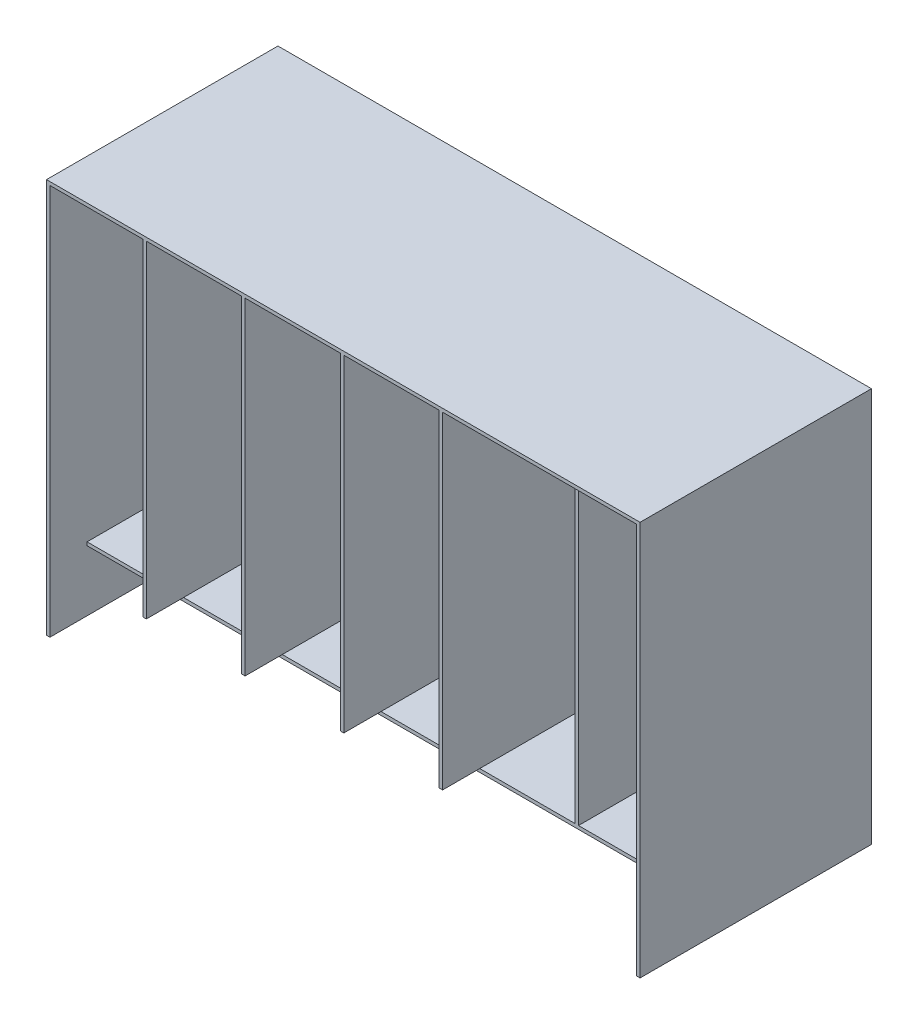
SolidWorks part; units mm, degrees
material "6061-T6 (SS)"
ref_plane "X-Y Datum" through (0, 0, 0) normal (0, 0, 1) x (1, 0, 0)
ref_plane "X-Z Datum" through (0, 0, 0) normal (0, 1, 0) x (1, 0, 0)
ref_plane "Y-Z Datum" through (0, 0, 0) normal (1, 0, 0) x (0, 0, -1)
sketch "Sketch1" plane through (0, 0, 0) normal (0, 0, 1) x (1, 0, 0)
  line L0 (-276.2265, 0) -> (276.2265, 0) construction
  line L1 (-276.2265, 154.041) -> (276.2265, 154.041)
  line L2 (-276.2265, 154.041) -> (-276.2265, -154.041)
  line L3 (-276.2265, -154.041) -> (276.2265, -154.041)
  line L4 (276.2265, 154.041) -> (276.2265, -154.041)
  line L5 (-276.2265, 154.041) -> (276.2265, -154.041) construction
  line L6 (-276.2265, -154.041) -> (276.2265, 154.041) construction
  line L7 (-275.2105, 153.025) -> (-189.6105, 153.025) construction
  line L8 (-275.2105, 153.025) -> (-275.2105, -153.025) construction
  line L9 (-275.2105, -153.025) -> (-189.6105, -153.025) construction
  line L10 (-189.6105, 153.025) -> (-189.6105, -153.025) construction
  line L11 (-275.2105, 153.025) -> (-189.6105, -153.025) construction
  line L12 (-275.2105, -153.025) -> (-189.6105, 153.025) construction
  line L13 (-188.5945, -154.041) -> (-188.5945, 154.041)
  line L14 (-279.4015, 157.216) -> (279.4015, 157.216)
  line L15 (279.4015, 157.216) -> (279.4015, -157.216)
  line L16 (-279.4015, -157.216) -> (279.4015, -157.216)
  line L17 (-279.4015, 157.216) -> (-279.4015, -157.216)
  line L18 (-185.4195, -154.041) -> (-185.4195, 154.041)
  line L19 (-188.5945, 0) -> (-185.4195, 0) construction
  line L20 (-182.2465, 153.025) -> (-182.2465, -153.025) construction
  line L21 (-182.2465, 153.025) -> (-96.6465, 153.025) construction
  line L22 (-96.6465, 153.025) -> (-96.6465, -153.025) construction
  line L23 (-182.2465, -153.025) -> (-96.6465, -153.025) construction
  line L24 (-95.6305, -154.041) -> (-95.6305, 154.041)
  line L25 (-92.4555, -154.041) -> (-92.4555, 154.041)
  line L26 (-89.2825, 153.025) -> (-89.2825, -153.025) construction
  line L27 (-89.2825, 153.025) -> (-3.6825, 153.025) construction
  line L28 (-3.6825, 153.025) -> (-3.6825, -153.025) construction
  line L29 (-89.2825, -153.025) -> (-3.6825, -153.025) construction
  line L30 (-2.6665, -154.041) -> (-2.6665, 154.041)
  line L31 (0.5085, -154.041) -> (0.5085, 154.041)
  line L32 (3.6815, 153.025) -> (3.6815, -153.025) construction
  line L33 (3.6815, 153.025) -> (89.2815, 153.025) construction
  line L34 (89.2815, 153.025) -> (89.2815, -153.025) construction
  line L35 (3.6815, -153.025) -> (89.2815, -153.025) construction
  line L36 (90.2975, -154.041) -> (90.2975, 154.041)
  line L37 (93.4725, -154.041) -> (93.4725, 154.041)
  line L38 (96.6455, 153.025) -> (96.6455, -153.025) construction
  line L39 (96.6455, 153.025) -> (182.2455, 153.025) construction
  line L40 (182.2455, 153.025) -> (182.2455, -153.025) construction
  line L41 (96.6455, -153.025) -> (182.2455, -153.025) construction
  line L42 (183.2615, -154.041) -> (183.2615, 154.041)
  line L43 (186.4365, -154.041) -> (186.4365, 154.041)
  line L44 (-182.2465, -153.025) -> (-96.6465, 153.025) construction
  line L45 (-182.2465, 153.025) -> (-96.6465, -153.025) construction
  line L46 (-89.2825, -153.025) -> (-3.6825, 153.025) construction
  line L47 (-89.2825, 153.025) -> (-3.6825, -153.025) construction
  line L48 (3.6815, -153.025) -> (89.2815, 153.025) construction
  line L49 (3.6815, 153.025) -> (89.2815, -153.025) construction
  line L50 (96.6455, -153.025) -> (182.2455, 153.025) construction
  line L51 (96.6455, 153.025) -> (182.2455, -153.025) construction
  line L52 (-276.2265, -157.216) -> (-276.2265, -211.191)
  line L53 (-279.4015, -157.216) -> (279.4015, -157.216)
  line L54 (-279.4015, -157.216) -> (-279.4015, -214.366)
  line L55 (-279.4015, -214.366) -> (279.4015, -214.366)
  line L56 (279.4015, -157.216) -> (279.4015, -214.366)
  line L57 (-276.2265, -211.191) -> (276.2265, -211.191)
  line L58 (276.2265, -157.216) -> (276.2265, -211.191)
  point P0 (0, 0)
  point P6 (-232.4105, 0)
  point P23 (-187.007, 0)
  point P24 (-139.4465, 0)
  dimension "D1" = 306.05
  dimension "D2" = 85.6
  dimension "D3" = 1.016
  dimension "D4" = 1.016
  dimension "D5" = 1.016
  dimension "D8" = 45.4035
  dimension "D10" = 89.789
  dimension "D12" = 92.964
  dimension "D13" = 89.79
  dimension "D14" = 57.15
  dimension "D6" = 3.175
  dimension "D7" = 3.175
  dimension "D15" = 3.175
  dimension "D9" = 5
  dimension "D11" = 5
extrude "Boss-Extrude1" add sketch "Sketch1" along normal blind 3.175 contours L3 L13 L1 L2 | L3 L24 L1 L18 | L3 L18 L1 L13 | L14 L17 L16 L15 L1 L4 L3 L2 | L3 L30 L1 L25 | L3 L25 L1 L24 | L3 L36 L1 L31 | L3 L31 L1 L30 | L3 L42 L1 L37 | L3 L37 L1 L36 | L43 L3 L4 L1 | L3 L43 L1 L42 | L54 L53 L56 L55
sketch "Sketch2" plane through (0, 0, 3.175) normal (0, 0, 1) x (1, 0, 0)
  line L0 (-188.5945, -154.041) -> (-188.5945, 154.041) construction
  line L1 (-95.6305, -154.041) -> (-95.6305, 154.041) construction
  line L2 (-185.4195, -154.041) -> (-185.4195, 154.041) construction
  line L3 (90.2975, -154.041) -> (90.2975, 154.041) construction
  line L4 (276.2265, 154.041) -> (-276.2265, 154.041)
  line L5 (276.2265, -154.041) -> (276.2265, 154.041)
  line L6 (-276.2265, -154.041) -> (276.2265, -154.041)
  line L7 (-276.2265, 154.041) -> (-276.2265, -154.041)
  line L8 (276.2265, 154.041) -> (-276.2265, 154.041)
  line L9 (276.2265, -154.041) -> (276.2265, 154.041)
  line L10 (-276.2265, -154.041) -> (276.2265, -154.041)
  line L11 (-276.2265, 154.041) -> (-276.2265, -154.041)
  line L12 (-279.4015, -157.216) -> (279.4015, -157.216)
  line L13 (-279.4015, -157.216) -> (279.4015, -157.216) construction
  line L14 (279.4015, 157.216) -> (279.4015, -157.216) construction
  line L15 (-279.4015, 157.216) -> (279.4015, 157.216) construction
  line L16 (-279.4015, -157.216) -> (279.4015, -157.216)
  line L20 (0.5085, -154.041) -> (0.5085, 154.041) construction
  line L21 (-2.6665, -154.041) -> (-2.6665, 154.041) construction
  line L22 (-92.4555, -154.041) -> (-92.4555, 154.041) construction
  line L23 (186.4365, -154.041) -> (186.4365, 154.041) construction
  line L24 (183.2615, -154.041) -> (183.2615, 154.041) construction
  line L25 (93.4725, -154.041) -> (93.4725, 154.041) construction
  line L26 (-188.5945, -154.041) -> (-188.5945, 154.041)
  line L27 (-95.6305, -154.041) -> (-95.6305, 154.041)
  line L28 (-185.4195, -154.041) -> (-185.4195, 154.041)
  line L29 (90.2975, -154.041) -> (90.2975, 154.041)
  line L30 (0.5085, -154.041) -> (0.5085, 154.041)
  line L31 (-2.6665, -154.041) -> (-2.6665, 154.041)
  line L32 (-92.4555, -154.041) -> (-92.4555, 154.041)
  line L33 (186.4365, -154.041) -> (186.4365, 154.041)
  line L34 (183.2615, -154.041) -> (183.2615, 154.041)
  line L35 (93.4725, -154.041) -> (93.4725, 154.041)
  line L36 (-279.4015, 157.216) -> (-279.4015, -157.216) construction
  line L37 (-279.4015, -157.216) -> (279.4015, -157.216) construction
  line L38 (-279.4015, -157.216) -> (-279.4015, -214.366) construction
  line L39 (-279.4015, -214.366) -> (279.4015, -214.366) construction
  line L40 (279.4015, -157.216) -> (279.4015, -214.366) construction
  line L41 (-276.2265, -157.216) -> (-276.2265, -211.191) construction
  line L42 (-276.2265, -211.191) -> (276.2265, -211.191) construction
  line L43 (276.2265, -157.216) -> (276.2265, -211.191) construction
  line L44 (-276.2265, 154.041) -> (276.2265, 154.041) construction
  line L45 (276.2265, 154.041) -> (276.2265, -154.041) construction
  line L46 (-276.2265, -154.041) -> (276.2265, -154.041) construction
  line L47 (-276.2265, 154.041) -> (-276.2265, -154.041) construction
  line L48 (-188.5945, -154.041) -> (-188.5945, 154.041)
  line L49 (-95.6305, -154.041) -> (-95.6305, 154.041)
  line L50 (-185.4195, -154.041) -> (-185.4195, 154.041)
  line L51 (-279.4015, -157.216) -> (279.4015, -157.216)
  line L52 (279.4015, 157.216) -> (279.4015, -157.216)
  line L53 (-279.4015, 157.216) -> (279.4015, 157.216)
  line L54 (-279.4015, 157.216) -> (-279.4015, -157.216)
  line L55 (-279.4015, -157.216) -> (279.4015, -157.216)
  line L56 (-279.4015, -157.216) -> (-279.4015, -214.366)
  line L57 (-279.4015, -214.366) -> (279.4015, -214.366)
  line L58 (279.4015, -157.216) -> (279.4015, -214.366)
  line L59 (90.2975, -154.041) -> (90.2975, 154.041)
  line L60 (0.5085, -154.041) -> (0.5085, 154.041)
  line L61 (-2.6665, -154.041) -> (-2.6665, 154.041)
  line L62 (-92.4555, -154.041) -> (-92.4555, 154.041)
  line L63 (186.4365, -154.041) -> (186.4365, 154.041)
  line L64 (183.2615, -154.041) -> (183.2615, 154.041)
  line L65 (93.4725, -154.041) -> (93.4725, 154.041)
  line L66 (-276.2265, -157.216) -> (-276.2265, -211.191)
  line L67 (-276.2265, -211.191) -> (276.2265, -211.191)
  line L68 (276.2265, -157.216) -> (276.2265, -211.191)
  line L69 (-276.2265, 154.041) -> (276.2265, 154.041)
  line L70 (276.2265, 154.041) -> (276.2265, -154.041)
  line L71 (-276.2265, -154.041) -> (276.2265, -154.041)
  line L72 (-276.2265, 154.041) -> (-276.2265, -154.041)
  dimension "D1" = 0
  dimension "D2" = 0
extrude "Boss-Extrude2" add sketch "Sketch2" along normal blind 176.6
sketch "Sketch4" plane through (0, -214.366, 0) normal (0, -1, 0) x (1, 0, 0)
  line L0 (-276.2265, 179.775) -> (-276.2265, 3.175)
  line L1 (-276.2265, 3.175) -> (276.2265, 3.175)
  line L2 (276.2265, 3.175) -> (276.2265, 179.775)
  line L4 (-279.4015, 0) -> (279.4015, 0)
  line L5 (279.4015, 0) -> (279.4015, 179.775)
  line L6 (279.4015, 179.775) -> (-279.4015, 179.775)
  line L7 (-279.4015, 179.775) -> (-279.4015, 0)
  line L8 (-279.4015, 0) -> (279.4015, 0)
  line L9 (279.4015, 0) -> (279.4015, 179.775)
  line L11 (-279.4015, 179.775) -> (-279.4015, 0)
  line L15 (279.4015, 179.775) -> (-279.4015, 179.775)
  dimension "D1" = 0
  dimension "D2" = 3.175
extrude "Cut-Extrude1" cut sketch "Sketch4" against normal blind 3.175
sketch "Sketch5" plane through (0, 0, 179.775) normal (0, 0, 1) x (1, 0, 0)
  line L0 (-188.5945, -154.041) -> (-188.5945, 154.041) construction
  line L1 (-95.6305, -154.041) -> (-95.6305, 154.041) construction
  line L2 (-185.4195, -154.041) -> (-185.4195, 154.041) construction
  line L3 (-279.4015, -157.216) -> (279.4015, -157.216) construction
  line L4 (279.4015, 157.216) -> (279.4015, -157.216) construction
  line L5 (-279.4015, 157.216) -> (279.4015, 157.216) construction
  line L6 (-279.4015, 157.216) -> (-279.4015, -157.216) construction
  line L7 (-279.4015, -157.216) -> (279.4015, -157.216) construction
  line L8 (-279.4015, -157.216) -> (-279.4015, -214.366) construction
  line L9 (-279.4015, -214.366) -> (279.4015, -214.366) construction
  line L10 (279.4015, -157.216) -> (279.4015, -214.366) construction
  line L11 (90.2975, -154.041) -> (90.2975, 154.041) construction
  line L12 (0.5085, -154.041) -> (0.5085, 154.041) construction
  line L13 (-2.6665, -154.041) -> (-2.6665, 154.041) construction
  line L14 (-92.4555, -154.041) -> (-92.4555, 154.041) construction
  line L15 (186.4365, -154.041) -> (186.4365, 154.041) construction
  line L16 (183.2615, -154.041) -> (183.2615, 154.041) construction
  line L17 (93.4725, -154.041) -> (93.4725, 154.041) construction
  line L18 (-276.2265, -157.216) -> (-276.2265, -211.191) construction
  line L19 (-276.2265, -211.191) -> (276.2265, -211.191) construction
  line L20 (276.2265, -157.216) -> (276.2265, -211.191) construction
  line L21 (-276.2265, 154.041) -> (276.2265, 154.041) construction
  line L22 (276.2265, 154.041) -> (276.2265, -154.041) construction
  line L23 (-276.2265, -154.041) -> (276.2265, -154.041) construction
  line L24 (-276.2265, 154.041) -> (-276.2265, -154.041) construction
  line L25 (-188.5945, -154.041) -> (-188.5945, 154.041)
  line L26 (-95.6305, -154.041) -> (-95.6305, 154.041)
  line L27 (-185.4195, -154.041) -> (-185.4195, 154.041)
  line L28 (-279.4015, -157.216) -> (279.4015, -157.216)
  line L29 (279.4015, 157.216) -> (279.4015, -157.216)
  line L30 (-279.4015, 157.216) -> (279.4015, 157.216)
  line L31 (-279.4015, 157.216) -> (-279.4015, -157.216)
  line L32 (-279.4015, -157.216) -> (279.4015, -157.216)
  line L33 (-279.4015, -157.216) -> (-279.4015, -214.366)
  line L34 (-279.4015, -214.366) -> (279.4015, -214.366)
  line L35 (279.4015, -157.216) -> (279.4015, -214.366)
  line L36 (90.2975, -154.041) -> (90.2975, 154.041)
  line L37 (0.5085, -154.041) -> (0.5085, 154.041)
  line L38 (-2.6665, -154.041) -> (-2.6665, 154.041)
  line L39 (-92.4555, -154.041) -> (-92.4555, 154.041)
  line L40 (186.4365, -154.041) -> (186.4365, 154.041)
  line L41 (183.2615, -154.041) -> (183.2615, 154.041)
  line L42 (93.4725, -154.041) -> (93.4725, 154.041)
  line L43 (-276.2265, -157.216) -> (-276.2265, -211.191)
  line L44 (-276.2265, -211.191) -> (276.2265, -211.191)
  line L45 (276.2265, -157.216) -> (276.2265, -211.191)
  line L46 (-276.2265, 154.041) -> (276.2265, 154.041)
  line L47 (276.2265, 154.041) -> (276.2265, -154.041)
  line L48 (-276.2265, -154.041) -> (276.2265, -154.041)
  line L49 (-276.2265, 154.041) -> (-276.2265, -154.041)
extrude "Boss-Extrude5" add sketch "Sketch5" along normal blind 38.1
sketch "Sketch7" plane through (0, 0, 217.875) normal (0, 0, 1) x (1, 0, 0)
  line L0 (-188.5945, -154.041) -> (-188.5945, 154.041) construction
  line L1 (-95.6305, -154.041) -> (-95.6305, 154.041) construction
  line L2 (-185.4195, -154.041) -> (-185.4195, 154.041) construction
  line L3 (-279.4015, -157.216) -> (279.4015, -157.216) construction
  line L4 (279.4015, 157.216) -> (279.4015, -157.216) construction
  line L5 (-279.4015, 157.216) -> (279.4015, 157.216) construction
  line L6 (-279.4015, 157.216) -> (-279.4015, -157.216) construction
  line L7 (-279.4015, -157.216) -> (279.4015, -157.216) construction
  line L8 (-279.4015, -157.216) -> (-279.4015, -214.366) construction
  line L9 (-279.4015, -214.366) -> (279.4015, -214.366) construction
  line L10 (279.4015, -157.216) -> (279.4015, -214.366) construction
  line L11 (90.2975, -154.041) -> (90.2975, 154.041) construction
  line L12 (0.5085, -154.041) -> (0.5085, 154.041) construction
  line L13 (-2.6665, -154.041) -> (-2.6665, 154.041) construction
  line L14 (-92.4555, -154.041) -> (-92.4555, 154.041) construction
  line L15 (186.4365, -154.041) -> (186.4365, 154.041) construction
  line L16 (183.2615, -154.041) -> (183.2615, 154.041) construction
  line L17 (93.4725, -154.041) -> (93.4725, 154.041) construction
  line L18 (-276.2265, -157.216) -> (-276.2265, -211.191) construction
  line L19 (-276.2265, -211.191) -> (276.2265, -211.191) construction
  line L20 (276.2265, -157.216) -> (276.2265, -211.191) construction
  line L21 (-276.2265, 154.041) -> (276.2265, 154.041) construction
  line L22 (276.2265, 154.041) -> (276.2265, -154.041) construction
  line L23 (-276.2265, -154.041) -> (276.2265, -154.041) construction
  line L24 (-276.2265, 154.041) -> (-276.2265, -154.041) construction
  line L25 (-188.5945, -154.041) -> (-188.5945, 154.041)
  line L26 (-95.6305, -154.041) -> (-95.6305, 154.041)
  line L27 (-185.4195, -154.041) -> (-185.4195, 154.041)
  line L28 (-279.4015, -157.216) -> (279.4015, -157.216)
  line L29 (279.4015, 157.216) -> (279.4015, -157.216)
  line L30 (-279.4015, 157.216) -> (279.4015, 157.216)
  line L31 (-279.4015, 157.216) -> (-279.4015, -157.216)
  line L32 (-279.4015, -157.216) -> (279.4015, -157.216)
  line L33 (-279.4015, -157.216) -> (-279.4015, -214.366)
  line L34 (-279.4015, -214.366) -> (279.4015, -214.366)
  line L35 (279.4015, -157.216) -> (279.4015, -214.366)
  line L36 (90.2975, -154.041) -> (90.2975, 154.041)
  line L37 (0.5085, -154.041) -> (0.5085, 154.041)
  line L38 (-2.6665, -154.041) -> (-2.6665, 154.041)
  line L39 (-92.4555, -154.041) -> (-92.4555, 154.041)
  line L40 (186.4365, -154.041) -> (186.4365, 154.041)
  line L41 (183.2615, -154.041) -> (183.2615, 154.041)
  line L42 (93.4725, -154.041) -> (93.4725, 154.041)
  line L43 (-276.2265, -157.216) -> (-276.2265, -211.191)
  line L44 (-276.2265, -211.191) -> (276.2265, -211.191)
  line L45 (276.2265, -157.216) -> (276.2265, -211.191)
  line L46 (-276.2265, 154.041) -> (276.2265, 154.041)
  line L47 (276.2265, 154.041) -> (276.2265, -154.041)
  line L48 (-276.2265, -154.041) -> (276.2265, -154.041)
  line L49 (-276.2265, 154.041) -> (-276.2265, -154.041)
  line L50 (-276.2265, -154.041) -> (-276.2265, -157.216)
  line L51 (276.2265, -154.041) -> (276.2265, -157.216)
  line L52 (183.2615, -154.041) -> (186.4365, -154.041)
  line L53 (183.2615, 154.041) -> (186.4365, 154.041)
  line M1 (-95.6305, -154.041) -> (-185.4195, -154.041)
  line M5 (-2.6665, -154.041) -> (-92.4555, -154.041)
  line M9 (90.2975, -154.041) -> (0.5085, -154.041)
  line M13 (183.2615, -154.041) -> (93.4725, -154.041)
  line M16 (183.2615, 154.041) -> (183.2615, -154.041)
  line M17 (276.2265, -154.041) -> (186.4365, -154.041)
  line M18 (186.4365, -154.041) -> (186.4365, 154.041)
  line M21 (-188.5945, -154.041) -> (-276.2265, -154.041)
  line M28 (-276.2265, -157.216) -> (276.2265, -157.216)
extrude "Cut-Extrude2" cut sketch "Sketch7" against normal blind 35 contours L51 L48 L50 M17 M13 M9 M5 M1 M21 M28 | L48 L46 M16 M18
